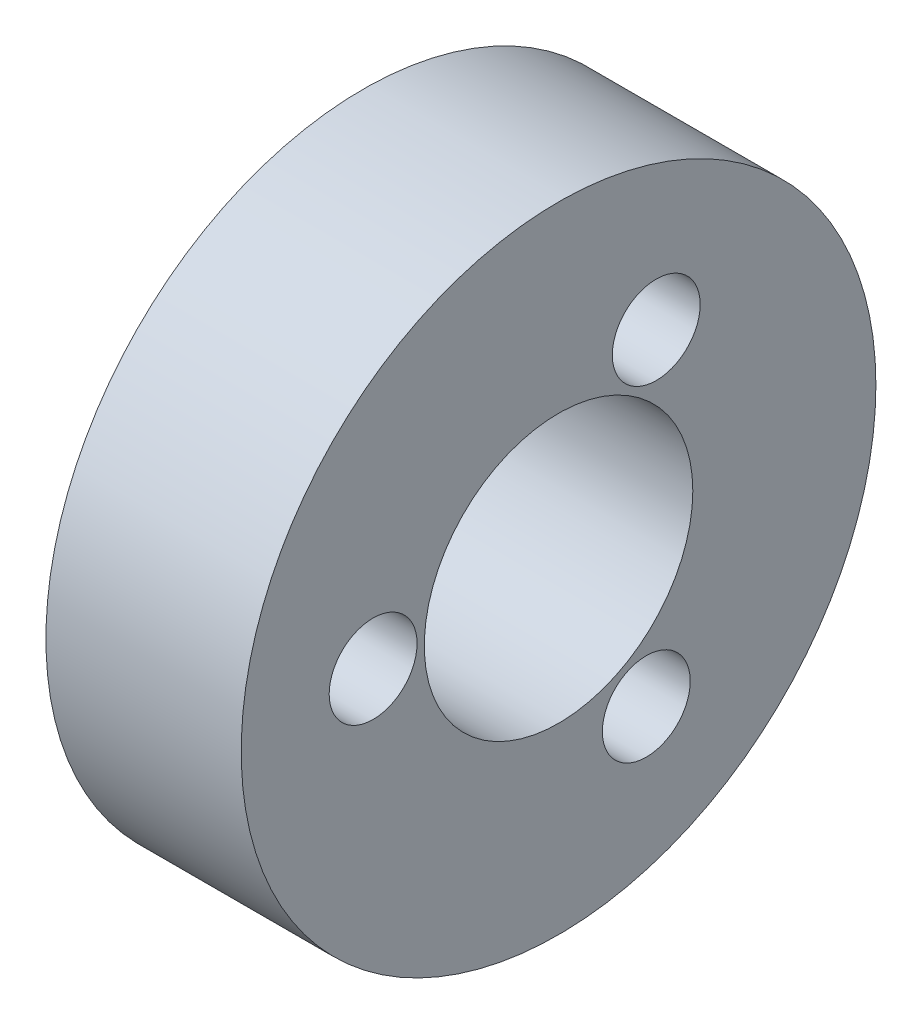
SolidWorks part; units mm, degrees
ref_plane "Front Plane" through (0, 0, 0) normal (0, 0, 1) x (1, 0, 0)
ref_plane "Top Plane" through (0, 0, 0) normal (0, 1, 0) x (1, 0, 0)
ref_plane "Right Plane" through (0, 0, 0) normal (1, 0, 0) x (0, 0, -1)
sketch "Sketch1" plane through (0, 0, 0) normal (1, 0, 0) x (0, 0, -1)
  circle A0 centre (0, 0) radius 6.5
  dimension "D1" = 13
extrude "Boss-Extrude1" add sketch "Sketch1" along normal blind 4
sketch "Sketch2" plane through (4, 0, 0) normal (1, 0, 0) x (0, 0, -1)
  circle A0 centre (0, 0) radius 2.75
  dimension "D1" = 5.5
extrude "Cut-Extrude1" cut sketch "Sketch2" against normal blind 7
sketch "Sketch3" plane through (0, 0, 0) normal (-1, 0, 0) x (0, 0, 1)
  circle A0 centre (-2.001, 3.2305) radius 0.9
  circle A1 centre (0, 0) radius 6.5 construction
  circle A2 centre (3.7982, 0.1177) radius 0.9
  circle A3 centre (-1.7972, -3.3482) radius 0.9
  point P10 (0, 0)
  dimension "D1" = 3.8
  dimension "D2" = 1.8
  dimension "D3" = 3
extrude "Cut-Extrude2" cut sketch "Sketch3" against normal blind 7
